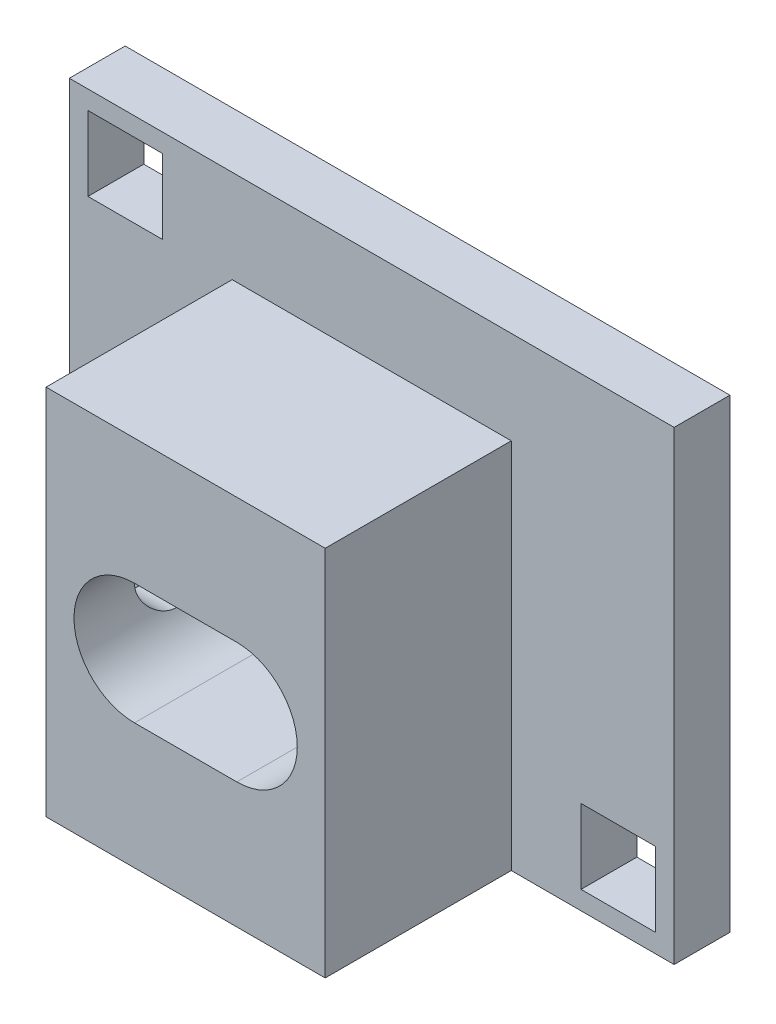
SolidWorks part; units mm, degrees
ref_plane "Спереди" through (0, 0, 0) normal (0, 0, 1) x (1, 0, 0)
ref_plane "Сверху" through (0, 0, 0) normal (0, 1, 0) x (1, 0, 0)
ref_plane "Справа" through (0, 0, 0) normal (1, 0, 0) x (0, 0, -1)
sketch "Эскиз1" plane through (0, 0, 0) normal (0, 0, 1) x (1, 0, 0)
  line L1 (-32.5, -25) -> (32.5, -25)
  line L2 (-32.5, -25) -> (-32.5, 25)
  line L3 (-32.5, 25) -> (32.5, 25)
  line L4 (32.5, -25) -> (32.5, 25)
  line L5 (-32.5, -25) -> (32.5, 25) construction
  line L6 (-32.5, 25) -> (32.5, -25) construction
  point P0 (0, 0)
  dimension "D1" = 65
  dimension "D2" = 50
extrude "Бобышка-Вытянуть1" add sketch "Эскиз1" along normal blind 6
sketch "Эскиз2" plane through (0, 0, 6) normal (0, 0, 1) x (1, 0, 0)
  line L0 (32.5, 25) -> (-32.5, 25) construction
  line L1 (-30.5, 15) -> (-22.5, 15)
  line L2 (-30.5, 15) -> (-30.5, 23)
  line L3 (-30.5, 23) -> (-22.5, 23)
  line L4 (-22.5, 15) -> (-22.5, 23)
  line L5 (-30.5, 15) -> (-22.5, 23) construction
  line L6 (-30.5, 23) -> (-22.5, 15) construction
  line L7 (-32.5, 25) -> (-32.5, -25) construction
  line L8 (-32.5, -25) -> (32.5, -25) construction
  line L9 (30.5, -23) -> (22.5, -23)
  line L10 (30.5, -23) -> (30.5, -15)
  line L11 (30.5, -15) -> (22.5, -15)
  line L12 (22.5, -23) -> (22.5, -15)
  line L13 (32.5, -25) -> (32.5, 25) construction
  point P0 (-26.5, 19)
  dimension "D1" = 8
  dimension "D2" = 8
  dimension "D3" = 2
  dimension "D4" = 2
  dimension "D5" = 2
  dimension "D6" = 2
extrude "Вырез-Вытянуть1" cut sketch "Эскиз2" against normal through all
sketch "Эскиз3" plane through (0, 0, 6) normal (0, 0, 1) x (1, 0, 0)
  line L0 (-32.5, -25) -> (32.5, -25) construction
  line L1 (-15, 15) -> (15, 15)
  line L2 (-15, 15) -> (-15, -25)
  line L3 (-15, -25) -> (15, -25)
  line L4 (15, 15) -> (15, -25)
  line L5 (-15, 15) -> (15, -25) construction
  line L6 (-15, -25) -> (15, 15) construction
  point P0 (0, -5)
  dimension "D1" = 40
  dimension "D2" = 30
extrude "Бобышка-Вытянуть2" add sketch "Эскиз3" along normal blind 20
sketch "Эскиз4" plane through (0, 0, 26) normal (0, 0, 1) x (1, 0, 0)
  line L0 (-15, -5) -> (15, -5) construction
  line L1 (-15, 15) -> (-15, -25) construction
  line L2 (15, -25) -> (15, 15) construction
  line L3 (-5.5, -5) -> (5.5, -5) construction
  line L4 (-5.5, 1.5) -> (5.5, 1.5)
  line L5 (-5.5, -11.5) -> (5.5, -11.5)
  arc A0 (-5.5, 1.5) -> (-5.5, -11.5) centre (-5.5, -5) ccw
  arc A1 (5.5, -11.5) -> (5.5, 1.5) centre (5.5, -5) ccw
  point P8 (0, -5)
  dimension "D1" = 13
  dimension "D2" = 11
extrude "Вырез-Вытянуть2" cut sketch "Эскиз4" against normal up to surface (20 mm away) up to face at (-26.5, 19, 6)
sketch "Эскиз5" plane through (-15, 0, 0) normal (-1, 0, 0) x (0, 0, 1)
  line L0 (26, -5) -> (6, -5) construction
  line L1 (26, 15) -> (26, -25) construction
  line L2 (6, 15) -> (6, -25) construction
  circle A0 centre (16, -5) radius 3.5
  dimension "D1" = 7
extrude "Вырез-Вытянуть3" cut sketch "Эскиз5" against normal up to surface (4.0228 mm away)
